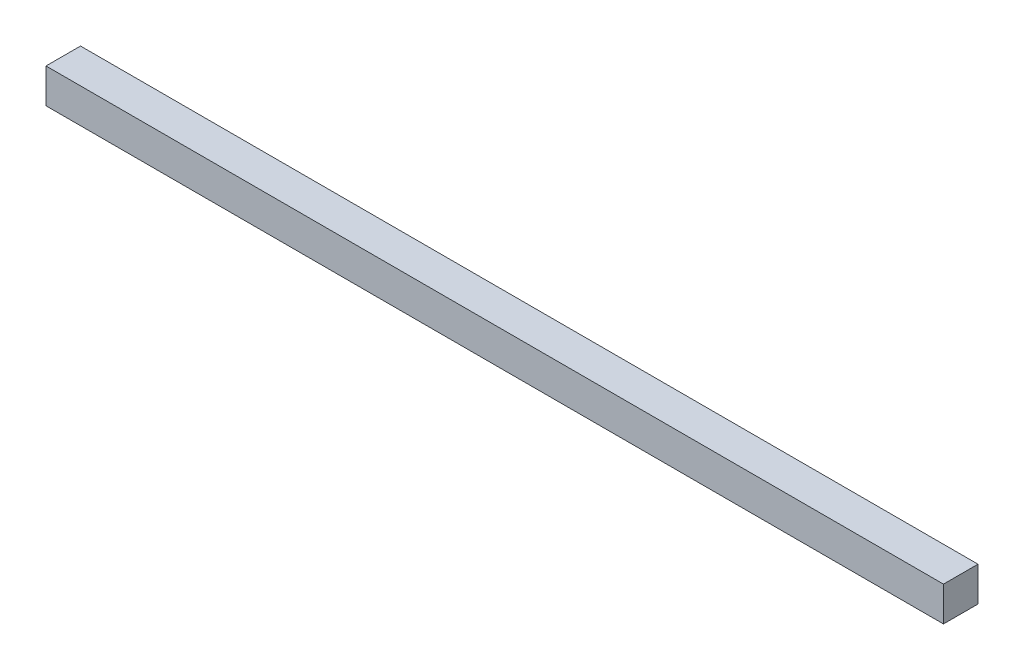
SolidWorks part; units mm, degrees
ref_plane "前视基准面" through (0, 0, 0) normal (0, 0, 1) x (1, 0, 0)
ref_plane "上视基准面" through (0, 0, 0) normal (0, 1, 0) x (1, 0, 0)
ref_plane "右视基准面" through (0, 0, 0) normal (1, 0, 0) x (0, 0, -1)
other "Configuration Table"
sketch "草图1" plane through (0, 0, 0) normal (0, 0, 1) x (1, 0, 0)
  line L0 (0, 0) -> (650, 0)
  line L1 (650, 0) -> (650, 25)
  line L2 (650, 25) -> (0, 25)
  line L3 (0, 25) -> (0, 0)
  dimension "width" = 650
  dimension "height" = 25
extrude "BlockExtrude" add sketch "草图1" along normal blind 25
